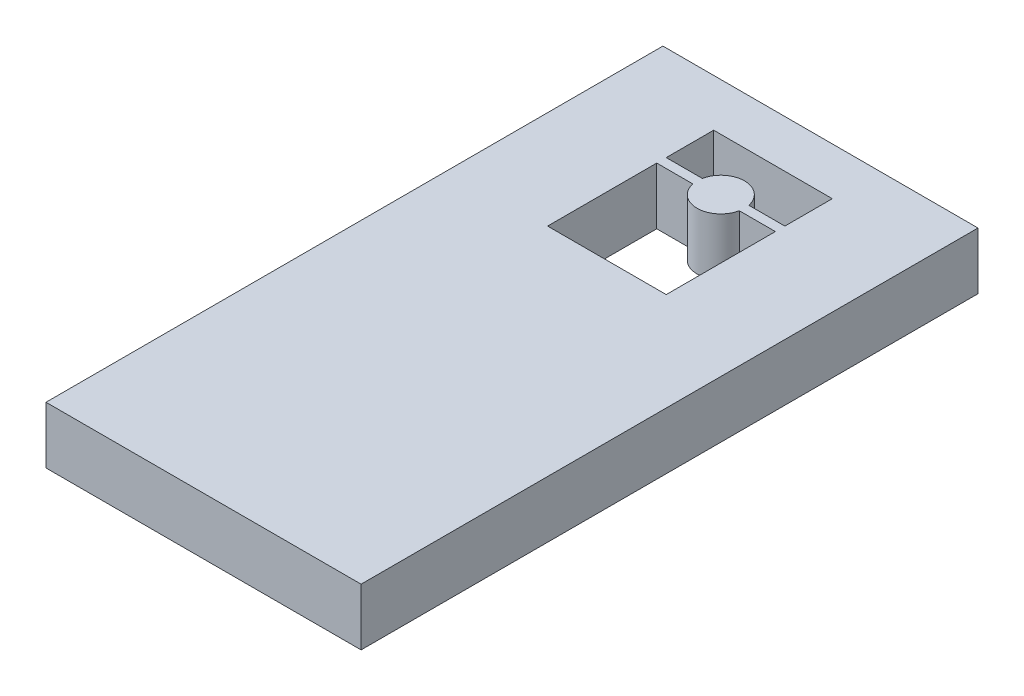
SolidWorks part; units mm, degrees
ref_plane "前视基准面" through (0, 0, 0) normal (0, 0, 1) x (1, 0, 0)
ref_plane "上视基准面" through (0, 0, 0) normal (0, 1, 0) x (1, 0, 0)
ref_plane "右视基准面" through (0, 0, 0) normal (1, 0, 0) x (0, 0, -1)
sketch "Sketch1" plane through (0, 0, 0) normal (0, 1, 0) x (1, 0, 0)
  line L1 (0, 0) -> (66.4, 0)
  line L2 (0, 0) -> (0, 130)
  line L3 (0, 130) -> (66.4, 130)
  line L4 (66.4, 0) -> (66.4, 130)
  dimension "D1" = 130
  dimension "D2" = 66.4
extrude "Boss-Extrude1" add sketch "Sketch1" along normal blind 12
sketch "Sketch2" plane through (0, 12, 0) normal (0, 1, 0) x (1, 0, 0)
  line L0 (66.4, 130) -> (0, 130) construction
  line L1 (20.7, 130) -> (45.7, 130)
  line L2 (20.7, 130) -> (20.7, 85)
  line L3 (20.7, 85) -> (45.7, 85)
  line L4 (45.7, 130) -> (45.7, 85)
  line L5 (0, 130) -> (0, 0) construction
  dimension "D1" = 25
  dimension "D2" = 20.7
  dimension "D3" = 45
extrude "Cut-Extrude2" cut sketch "Sketch2" against normal blind 20
sketch "Sketch3" plane through (0, 12, 0) normal (0, 1, 0) x (1, 0, 0)
  line L0 (45.7, 85) -> (45.7, 130) construction
  line L1 (20.7, 130) -> (45.7, 130)
  line L2 (20.7, 130) -> (20.7, 120)
  line L3 (20.7, 120) -> (45.7, 120)
  line L4 (45.7, 130) -> (45.7, 120)
  dimension "D1" = 10
extrude "Boss-Extrude2" add sketch "Sketch3" against normal blind 12
sketch "Sketch4" plane through (0, 12, 0) normal (0, 1, 0) x (1, 0, 0)
  line L0 (66.4, 130) -> (0, 130) construction
  line L2 (20.7, 120) -> (20.7, 85) construction
  circle A0 centre (33.2, 109) radius 5
  dimension "D2" = 10
  dimension "D1" = 21
  dimension "D3" = 12.5
extrude "Boss-Extrude4" add sketch "Sketch4" against normal blind 12 separate body
sketch "Sketch5" plane through (0, 12, 0) normal (0, 1, 0) x (1, 0, 0)
  line L0 (20.7, 120) -> (20.7, 85) construction
  line L1 (20.7, 110) -> (45.7, 110)
  line L2 (20.7, 110) -> (20.7, 108)
  line L3 (20.7, 108) -> (45.7, 108)
  line L4 (45.7, 110) -> (45.7, 108)
  line L5 (45.7, 85) -> (45.7, 120) construction
  line L6 (66.4, 130) -> (0, 130) construction
  dimension "D1" = 20
  dimension "D2" = 22
extrude "Boss-Extrude5" add sketch "Sketch5" against normal blind 12
